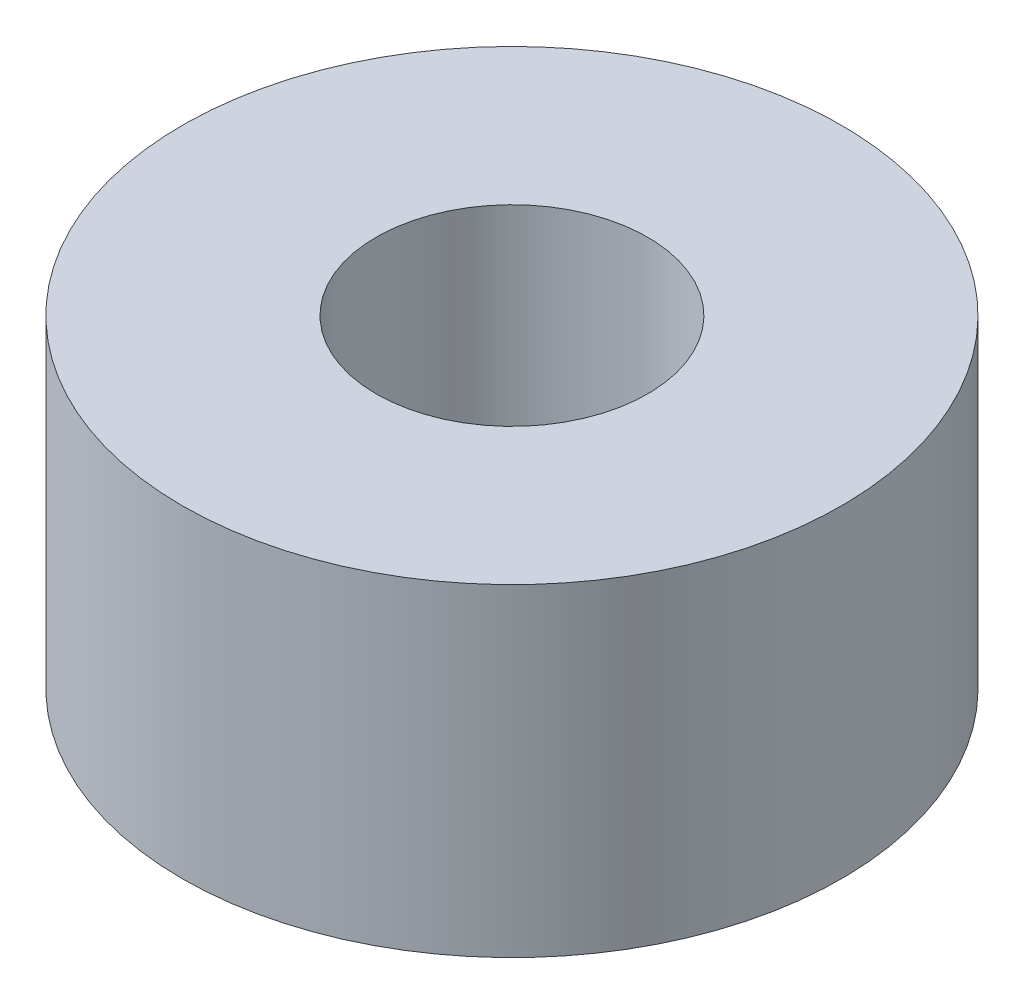
SolidWorks part; units mm, degrees
ref_plane "Front Plane" through (0, 0, 0) normal (0, 0, 1) x (1, 0, 0)
ref_plane "Top Plane" through (0, 0, 0) normal (0, 1, 0) x (1, 0, 0)
ref_plane "Right Plane" through (0, 0, 0) normal (1, 0, 0) x (0, 0, -1)
sketch "Sketch1" plane through (0, 0, 0) normal (0, 1, 0) x (1, 0, 0)
  circle A0 centre (0, 0) radius 5.1016
  circle A1 centre (0, 0) radius 2.1016
  dimension "D1" = 4.2032
  dimension "D2" = 3
extrude "Boss-Extrude1" add sketch "Sketch1" along normal blind 5
